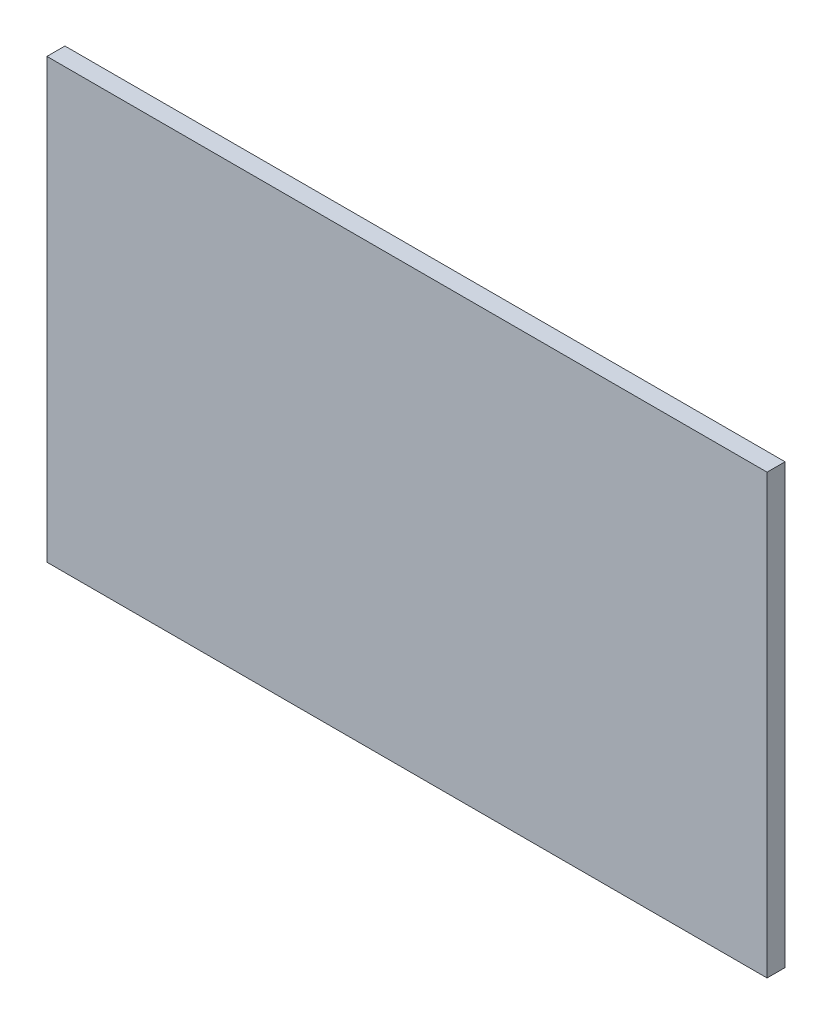
SolidWorks part; units mm, degrees
ref_plane "前视基准面" through (0, 0, 0) normal (0, 0, 1) x (1, 0, 0)
ref_plane "上视基准面" through (0, 0, 0) normal (0, 1, 0) x (1, 0, 0)
ref_plane "右视基准面" through (0, 0, 0) normal (1, 0, 0) x (0, 0, -1)
other "Configuration Table"
sketch "草图1" plane through (0, 0, 0) normal (0, 0, 1) x (1, 0, 0)
  line L1 (-60, -36.5) -> (60, -36.5)
  line L2 (-60, -36.5) -> (-60, 36.5)
  line L3 (-60, 36.5) -> (60, 36.5)
  line L4 (60, -36.5) -> (60, 36.5)
  line L5 (-60, -36.5) -> (60, 36.5) construction
  line L6 (-60, 36.5) -> (60, -36.5) construction
  point P0 (0, 0)
  dimension "D1" = 73
  dimension "D2" = 120
extrude "凸台-拉伸1" add sketch "草图1" along normal blind 3
